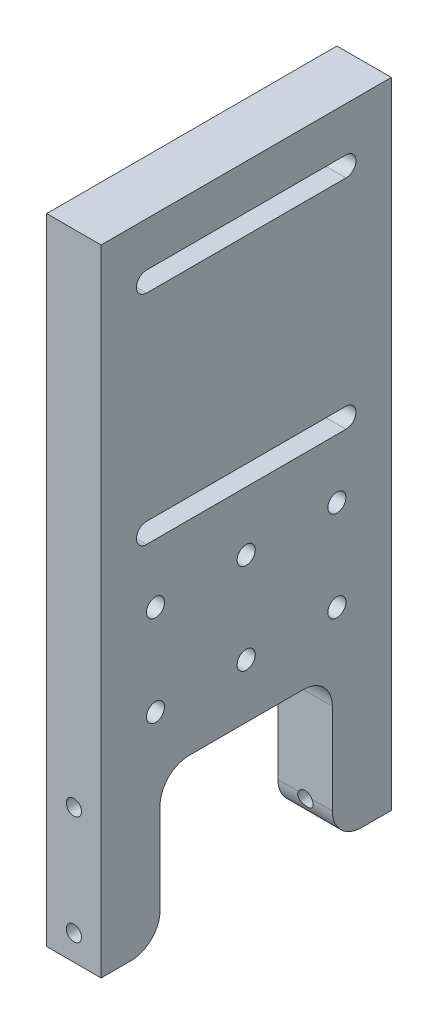
SolidWorks part; units mm, degrees
ref_plane "Front" through (0, 0, 0) normal (0, 0, 1) x (1, 0, 0)
ref_plane "Top" through (0, 0, 0) normal (0, 1, 0) x (1, 0, 0)
ref_plane "Right" through (0, 0, 0) normal (1, 0, 0) x (0, 0, -1)
sketch "Esquisse1" plane through (0, 0, 0) normal (0, 0, 1) x (1, 0, 0)
  line L0 (44.7995, -9.626) -> (29.7995, -9.626)
  line L1 (44.7995, -9.626) -> (44.7995, 80.374)
  line L2 (29.7995, -9.626) -> (29.7995, 80.374)
  line L3 (44.7995, 80.374) -> (29.7995, 80.374)
  dimension "D1" = 15
  dimension "D2" = 90
  dimension "D3" = 20
extrude "Boss.-Extru.1" add sketch "Esquisse1" along normal blind 80
sketch "Esquisse2" plane through (44.7995, 0, 0) normal (1, 0, 0) x (0, 0, -1)
  line L0 (-63.75, -9.626) -> (-16.25, -9.626)
  line L1 (-63.75, -9.626) -> (-63.75, 31.374)
  line L2 (-16.25, -9.626) -> (-16.25, 31.374)
  line L3 (-63.75, 31.374) -> (-16.25, 31.374)
  line L4 (-80, -9.626) -> (0, -9.626) construction
  point P7 (-40, -9.626)
  point P8 (-40, -9.626)
  dimension "D1" = 47.5
  dimension "D2" = 41
extrude "Enlèv. mat.-Extru.1" cut sketch "Esquisse2" against normal through all
fillet "Congé1" radius 8 4 edges at (37.2995, 31.374, 63.75) (37.2995, -9.626, 16.25) (37.2995, 31.374, 16.25) (37.2995, -9.626, 63.75)
sketch "Esquisse3" plane through (29.7995, 0, 0) normal (-1, 0, 0) x (0, 0, 1)
  line L0 (0, 80.374) -> (80, 80.374)
  line L1 (0, 80.374) -> (0, 165.374)
  line L2 (80, 80.374) -> (80, 165.374)
  line L3 (0, 165.374) -> (80, 165.374)
  line L4 (0, 90.374) -> (80, 90.374) construction
  line L5 (12.5, 90.374) -> (67.5, 90.374) construction
  line L6 (12.5, 93.124) -> (67.5, 93.124)
  line L7 (12.5, 87.624) -> (67.5, 87.624)
  line L8 (0, 150.374) -> (80, 150.374) construction
  line L9 (12.5, 150.374) -> (67.5, 150.374) construction
  line L10 (12.5, 153.124) -> (67.5, 153.124)
  line L11 (12.5, 147.624) -> (67.5, 147.624)
  arc A2 (12.5, 93.124) -> (12.5, 87.624) centre (12.5, 90.374) ccw
  arc A3 (67.5, 87.624) -> (67.5, 93.124) centre (67.5, 90.374) ccw
  arc A4 (12.5, 153.124) -> (12.5, 147.624) centre (12.5, 150.374) ccw
  arc A5 (67.5, 147.624) -> (67.5, 153.124) centre (67.5, 150.374) ccw
  point P10 (40, 90.374)
  point P16 (40, 90.374)
  point P22 (40, 150.374)
  dimension "D1" = 5.5
  dimension "D2" = 55
  dimension "D4" = 60
  dimension "D5" = 85
  dimension "D6" = 10
  dimension "D3" = 2
extrude "Boss.-Extru.2" add sketch "Esquisse3" against normal blind 15
sketch "Esquisse4" plane through (0, 0, 80) normal (0, 0, 1) x (1, 0, 0)
  line L0 (37.2995, -9.626) -> (37.2995, 27.374) construction
  line L1 (29.7995, -9.626) -> (44.7995, -9.626) construction
  point P4 (37.2995, -2.626)
  dimension "D1" = 7
  dimension "D2" = 30
hole_wizard "Trou taraudé M5x0.81" positions "Esquisse3D1" profile "Esquisse5" tap size "M5x0.8" standard "Ansi Metric" end condition through all
sketch3d "Esquisse3D1"
  point P0 (37.2995, -2.626, 80)
  point P3 (37.2995, 27.374, 80)
cosmetic thread "Filetage de perçage23" parameters "D2"=5
cosmetic thread "Filetage de perçage24" parameters "D2"=5
sketch "Esquisse5" plane through (37.2995, -2.626, 80) normal (1, 0, 0) x (0, -1, 0)
  line L0 (0, 0) -> (0, 80)
  line L1 (0, 80) -> (2.1, 80)
  line L2 (2.1, 80) -> (2.1, 0)
  line L5 (2.1, 0) -> (0, 0)
  line L11 (0, -6.35) -> (0, 107.95) construction
  dimension "Diamètre du trou pour taraudage jusqu'au prochain" = 4.2
  dimension "Profondeur du trou pour taraudage jusqu'au prochain" = 80
ref_plane "Plan1" through (0, 0, 40) normal (0, 0, 1) x (1, 0, 0)
mirror "Symétrie1" about plane through (0, 0, 40) normal (0, 0, 1) of "Trou taraudé M5x0.81"
cosmetic thread "Filetage de perçage25" parameters "D2"=5
cosmetic thread "Filetage de perçage26" parameters "D2"=5
sketch "Esquisse6" plane through (29.7995, 0, 0) normal (-1, 0, 0) x (0, 0, 1)
  line L0 (40, 31.374) -> (40, 46.374) construction
  line L1 (24.25, 31.374) -> (55.75, 31.374) construction
  line L2 (65, 46.374) -> (15, 46.374) construction
  point P7 (40, 46.374)
  dimension "D1" = 50
  dimension "D2" = 15
hole_wizard "Trou taraudé profond M6x1.01" positions "Esquisse3D2" profile "Esquisse8" tap size "M6x1.0" standard "HASCO Metric" end condition through all
sketch3d "Esquisse3D2"
  point P0 (29.7995, 46.374, 15)
  point P3 (29.7995, 46.374, 40)
  point P6 (29.7995, 46.374, 65)
cosmetic thread "Filetage de perçage14" parameters "D2"=6
cosmetic thread "Filetage de perçage15" parameters "D2"=6
cosmetic thread "Filetage de perçage16" parameters "D2"=6
sketch "Esquisse8" plane through (29.7995, 46.374, 15) normal (0, 1, 0) x (0, 0, 1)
  line L0 (0, 0) -> (0, 15)
  line L1 (0, 15) -> (2.5, 15)
  line L2 (2.5, 15) -> (2.5, 0)
  line L5 (2.5, 0) -> (0, 0)
  line L11 (0, -6.35) -> (0, 107.95) construction
  dimension "Diamètre du trou pour taraudage jusqu'au prochain" = 5
  dimension "Profondeur du trou pour taraudage jusqu'au prochain" = 15
pattern_linear "Répétition linéaire1" count 2 spacing 25 along (0, 1, 0) of "Trou taraudé profond M6x1.01"
cosmetic thread "Filetage de perçage17" parameters "D2"=6
cosmetic thread "Filetage de perçage18" parameters "D2"=6
cosmetic thread "Filetage de perçage19" parameters "D2"=6
cosmetic thread "Filetage de perçage20" parameters "D2"=6
cosmetic thread "Filetage de perçage21" parameters "D2"=6
cosmetic thread "Filetage de perçage22" parameters "D2"=6
